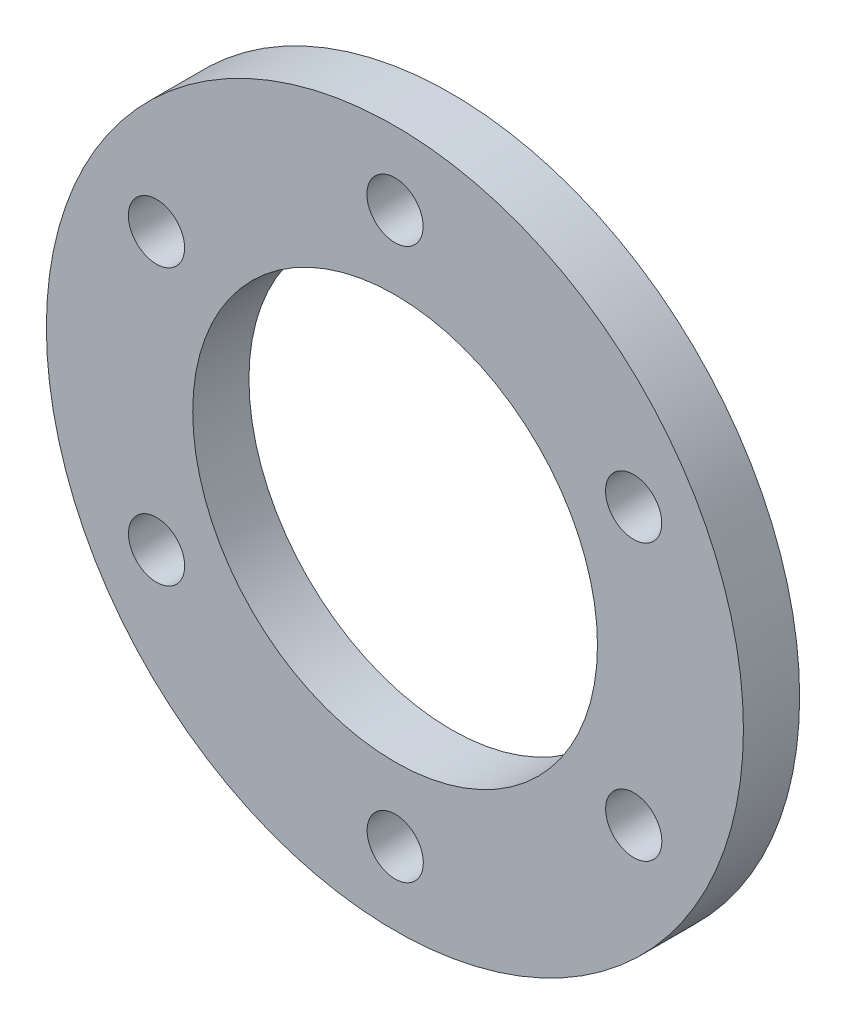
SolidWorks part; units mm, degrees
ref_plane "Front Plane" through (0, 0, 0) normal (0, 0, 1) x (1, 0, 0)
ref_plane "Top Plane" through (0, 0, 0) normal (0, 1, 0) x (1, 0, 0)
ref_plane "Right Plane" through (0, 0, 0) normal (1, 0, 0) x (0, 0, -1)
sketch "Sketch1" plane through (0, 0, 0) normal (0, 0, 1) x (1, 0, 0)
  circle A6 centre (-36.2755, 16.363) radius 18
  circle A7 centre (-36.2938, 16.369) radius 31
  dimension "D1" = 62
  dimension "D2" = 36
extrude "Boss-Extrude1" add sketch "Sketch1" along normal blind 5
sketch "Sketch2" plane through (0, 0, 5) normal (0, 0, 1) x (1, 0, 0)
  circle A3 centre (-36.2846, 40.866) radius 2.5
  circle A4 centre (-15.0598, 28.6224) radius 2.5
  circle A5 centre (-15.0507, 4.1194) radius 2.5
  circle A6 centre (-36.2664, -8.14) radius 2.5
  circle A7 centre (-57.4912, 4.1036) radius 2.5
  circle A8 centre (-57.5003, 28.6066) radius 2.5
  point P16 (-36.2755, 16.363)
  dimension "D1" = 5
  dimension "D2" = 6
extrude "Cut-Extrude1" cut sketch "Sketch2" against normal through all
